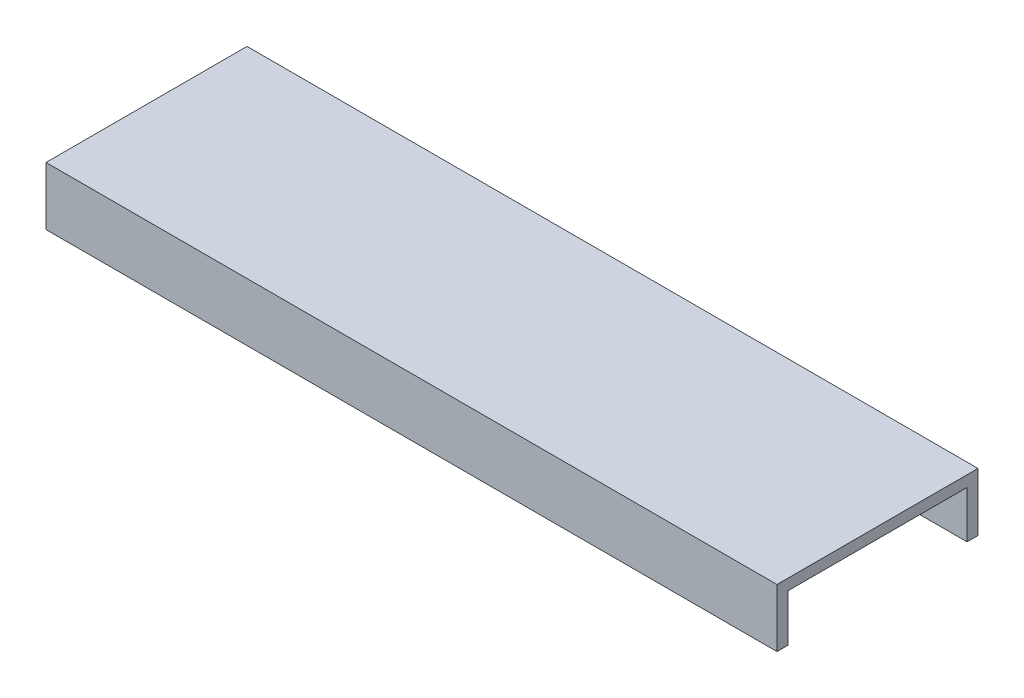
SolidWorks part; units mm, degrees
ref_plane "前视基准面" through (0, 0, 0) normal (0, 0, 1) x (1, 0, 0)
ref_plane "上视基准面" through (0, 0, 0) normal (0, 1, 0) x (1, 0, 0)
ref_plane "右视基准面" through (0, 0, 0) normal (1, 0, 0) x (0, 0, -1)
other "Configuration Table"
sketch "草图1" plane through (0, 0, 0) normal (1, 0, 0) x (0, 0, -1)
  line L0 (-13.75, 7.95) -> (-13.75, 0)
  line L1 (-12.25, 6.45) -> (12.25, 6.45)
  line L2 (-12.25, 6.45) -> (-12.25, 0)
  line L4 (12.25, 6.45) -> (12.25, 0)
  line L5 (-12.25, 6.45) -> (0, 0) construction
  line L6 (0, 0) -> (12.25, 6.45) construction
  line L8 (13.75, 7.95) -> (13.75, 0)
  line L9 (-13.75, 7.95) -> (13.75, 7.95)
  line L10 (-13.75, 0) -> (-12.25, 0)
  line L11 (-13.75, 7.95) -> (-13.75, -5.45) construction
  line L12 (-12.25, 6.45) -> (-12.25, -3.95) construction
  line L13 (12.25, 6.45) -> (12.25, -3.95) construction
  line L14 (13.75, 7.95) -> (13.75, -5.45) construction
  line L15 (-12.25, -3.95) -> (12.25, -3.95) construction
  line L16 (-13.75, -5.45) -> (13.75, -5.45) construction
  line L17 (12.25, 0) -> (13.75, 0)
  point P0 (0, 0)
  dimension "D2" = 24.5
  dimension "D3" = 6.45
  dimension "D1" = 1.5
extrude "凸台-拉伸1" add sketch "草图1" along normal blind 100
